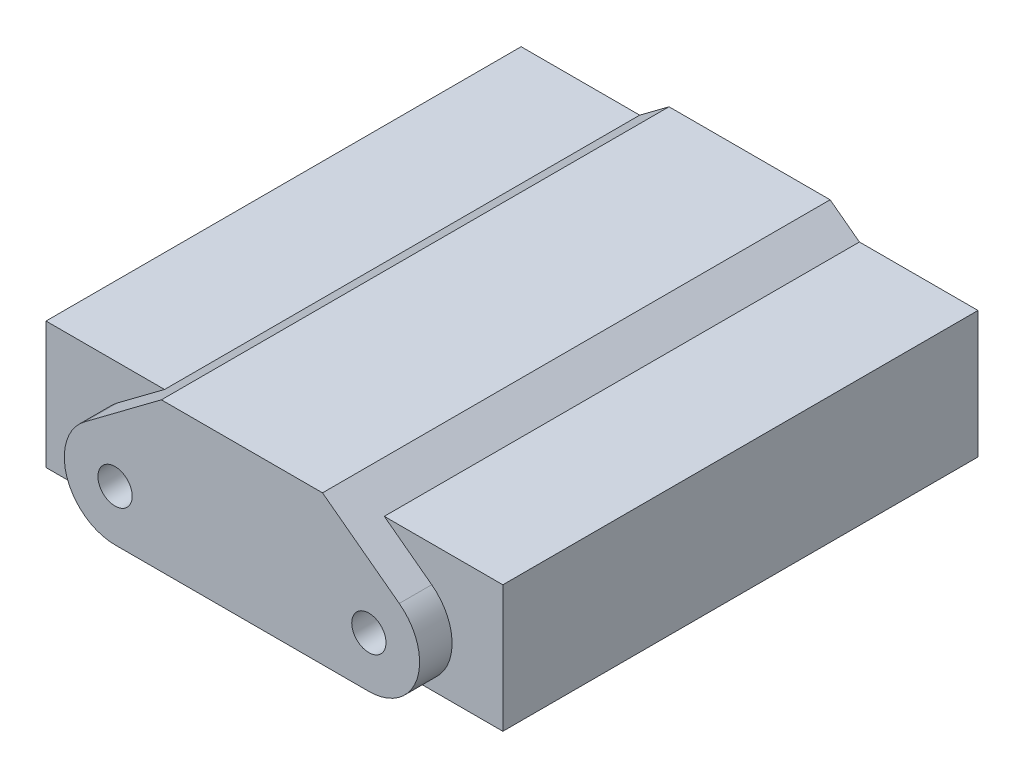
SolidWorks part; units mm, degrees
ref_plane "Front" through (0, 0, 0) normal (0, 0, 1) x (1, 0, 0)
ref_plane "Top" through (0, 0, 0) normal (0, 1, 0) x (1, 0, 0)
ref_plane "Right" through (0, 0, 0) normal (1, 0, 0) x (0, 0, -1)
sketch "草图1" plane through (0, 0, 0) normal (0, 0, 1) x (1, 0, 0)
  line L0 (-10, -4) -> (10, -4)
  line L2 (0, 7.727) -> (-6.3477, 7.727)
  line L3 (-6.3477, 7.727) -> (-12.3959, 3.2031)
  line L4 (0, 7.727) -> (6.3477, 7.727)
  line L5 (6.3477, 7.727) -> (12.3959, 3.2031)
  circle A1 centre (10, 0) radius 1.35
  circle A2 centre (-10, 0) radius 1.35
  arc A3 (-12.3959, 3.2031) -> (-10, -4) centre (-10, 0) ccw
  arc A4 (10, -4) -> (12.3959, 3.2031) centre (10, 0) ccw
  dimension "D1" = 20
extrude "凸台-拉伸1" add sketch "草图1" along normal blind 40
sketch "草图2" plane through (0, -4, 0) normal (0, -1, 0) x (1, 0, 0)
  line L1 (-10, 40) -> (-10, 0) construction
  line L2 (-10, 37.4417) -> (-18, 37.4417)
  line L3 (-18, 37.4417) -> (-18, 0)
  line L4 (-18, 0) -> (0, 0)
  line L5 (0, 0) -> (10, 0)
  line L6 (10, 0) -> (18, 0)
  line L7 (18, 0) -> (18, 37.4417)
  line L8 (18, 37.4417) -> (-10, 37.4417)
extrude "凸台-拉伸2" add sketch "草图2" against normal blind 10
sketch "草图3" plane through (0, -4, 0) normal (0, -1, 0) x (1, 0, 0)
  line L0 (-18, 37.4417) -> (18, 37.4417)
  line L1 (18, 37.4417) -> (18, 0)
  line L2 (18, 0) -> (-18, 0)
  line L3 (-18, 0) -> (-18, 37.4417)
  circle A0 centre (0, 16) radius 11
extrude "凸台-拉伸3" add sketch "草图3" along normal blind 5
sketch "草图7" plane through (0, -9, 0) normal (0, -1, 0) x (1, 0, 0)
  line L0 (-18, 37.4417) -> (18, 37.4417)
  line L1 (18, 37.4417) -> (18, 0)
  line L2 (18, 0) -> (18, 37.4417) construction
  line L3 (18, 0) -> (-18, 0)
  line L4 (-18, 0) -> (-18, 37.4417)
extrude "切除-拉伸4" cut sketch "草图7" against normal blind 5
sketch "草图8" plane through (0, 0, 37.4417) normal (0, 0, 1) x (1, 0, 0)
  circle A0 centre (10, 0) radius 1.35
  circle A1 centre (-10, 0) radius 1.35
extrude "切除-拉伸5" cut sketch "草图8" against normal blind 12
sketch "草图10" plane through (0, 0, 0) normal (0, 0, -1) x (-1, 0, 0)
  circle A1 centre (10, 0) radius 1.34
  circle A2 centre (-10, 0) radius 1.35
extrude "切除-拉伸6" cut sketch "草图10" against normal blind 52
